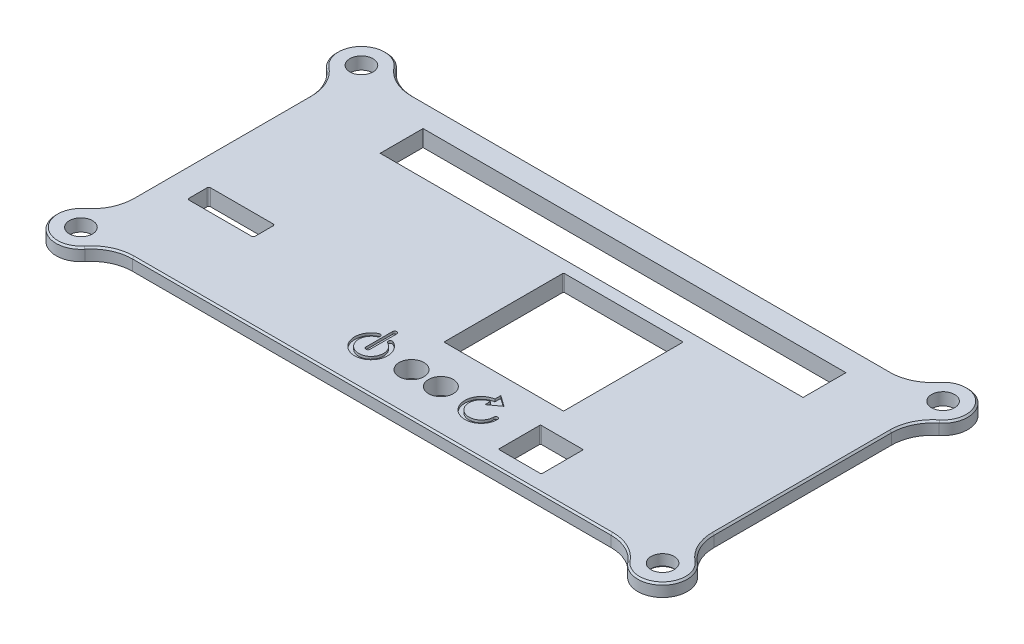
SolidWorks part; units mm, degrees
material "环氧树脂,未充填"
ref_plane "前视基准面" through (0, 0, 0) normal (0, 0, 1) x (1, 0, 0)
ref_plane "上视基准面" through (0, 0, 0) normal (0, 1, 0) x (1, 0, 0)
ref_plane "右视基准面" through (0, 0, 0) normal (1, 0, 0) x (0, 0, -1)
sketch "草图1" plane through (0, 0, 0) normal (0, 1, 0) x (1, 0, 0)
  line L1 (3, 0) -> (67.5, 0)
  line L2 (0, 3) -> (0, 31)
  line L3 (3, 34) -> (67.5, 34)
  line L4 (70.5, 3) -> (70.5, 31)
  arc A0 (3, 34) -> (0, 31) centre (0, 34) ccw
  arc A1 (70.5, 31) -> (67.5, 34) centre (70.5, 34) ccw
  arc A2 (0, 3) -> (3, 0) centre (0, 0) ccw
  arc A3 (67.5, 0) -> (70.5, 3) centre (70.5, 0) ccw
  circle A4 centre (0, 0) radius 1.4
  circle A5 centre (70.5, 0) radius 1.4
  circle A6 centre (70.5, 34) radius 1.4
  circle A7 centre (0, 34) radius 1.4
  dimension "D3" = 2.8
  dimension "D4" = 2.8
  dimension "D5" = 2.8
  dimension "D6" = 2.8
  dimension "D1" = 34
  dimension "D2" = 70.5
extrude "凸台-拉伸1" add sketch "草图1" along normal blind 1.5
fillet "圆角1" radius 5 8 edges at (67.5, 0.75, 0) (3, 0.75, 0) (0, 0.75, -3) (0, 0.75, -31) (3, 0.75, -34) (67.5, 0.75, -34) (70.5, 0.75, -31) (70.5, 0.75, -3)
sketch "草图9" plane through (0, 0, 0) normal (0, -1, 0) x (1, 0, 0)
  line L1 (3.2, -4.5) -> (3.2, -29.5)
  line L11 (66, -32.3) -> (6, -32.3)
  line L12 (68.8, -4.5) -> (68.8, -29.5)
  line L13 (6, -1.7) -> (66, -1.7)
  arc A13 (6, -32.3) -> (3.2, -29.5) centre (6, -29.5) cw
  arc A14 (3.2, -4.5) -> (6, -1.7) centre (6, -4.5) cw
  arc A15 (68.8, -4.5) -> (66, -1.7) centre (66, -4.5) ccw
  arc A16 (68.8, -29.5) -> (66, -32.3) centre (66, -29.5) cw
  dimension "D1" = 2.8
extrude "凸台-拉伸2" add sketch "草图9" along normal blind 0.5
sketch "草图2" plane through (0, 1.5, 0) normal (0, 1, 0) x (1, 0, 0)
  line L3 (48.45, 9.95) -> (34.15, 9.95)
  line L4 (48.55, 10.05) -> (48.55, 24.35)
  line L5 (48.45, 24.45) -> (34.15, 24.45)
  line L6 (34.05, 10.05) -> (34.05, 24.35)
  arc A0 (34.05, 10.05) -> (34.15, 9.95) centre (34.15, 10.05) ccw
  arc A1 (48.45, 9.95) -> (48.55, 10.05) centre (48.45, 10.05) ccw
  arc A2 (48.45, 24.45) -> (48.55, 24.35) centre (48.45, 24.35) cw
  arc A3 (34.15, 24.45) -> (34.05, 24.35) centre (34.15, 24.35) ccw
  point P8 (34.05, 9.95)
  point P11 (48.55, 9.95)
  point P14 (48.55, 24.45)
  dimension "D3" = 0.1
  dimension "D1" = 14.5
  dimension "D2" = 14.5
extrude "切除-拉伸1" cut sketch "草图2" against normal blind 2.5
sketch "草图3" plane through (0, 1.5, 0) normal (0, 1, 0) x (1, 0, 0)
  line L2 (10.37, 31.1) -> (10.37, 25.9)
  line L3 (61.63, 31.1) -> (10.37, 31.1)
  line L5 (61.63, 25.9) -> (10.37, 25.9)
  line L6 (61.63, 31.1) -> (61.63, 25.9)
  point P0 (62.8, 31.1)
  point P8 (62.8, 25.9)
  point P10 (9.2, 25.9)
  point P11 (9.2, 31.1)
extrude "切除-拉伸2" cut sketch "草图3" against normal blind 2.5
sketch "草图4" plane through (0, 1.5, 0) normal (0, 1, 0) x (1, 0, 0)
  line L0 (48.7, 7.1) -> (53.7, 7.1)
  line L1 (53.7, 2) -> (48.7, 2)
  line L2 (53.8, 2.1) -> (53.8, 7)
  line L3 (48.6, 2.1) -> (48.6, 7)
  arc A0 (48.6, 2.1) -> (48.7, 2) centre (48.7, 2.1) ccw
  arc A1 (53.7, 2) -> (53.8, 2.1) centre (53.7, 2.1) ccw
  arc A2 (53.8, 7) -> (53.7, 7.1) centre (53.7, 7) ccw
  arc A3 (48.7, 7.1) -> (48.6, 7) centre (48.7, 7) ccw
  dimension "D1" = 0.1
  dimension "D2" = 0.1
extrude "切除-拉伸3" cut sketch "草图4" against normal blind 2.5
sketch "草图5" plane through (0, 1.5, 0) normal (0, 1, 0) x (1, 0, 0)
  circle A0 centre (34.98, 5.09) radius 1.5
  circle A1 centre (38.54, 5.09) radius 1.5
extrude "切除-拉伸4" cut sketch "草图5" against normal blind 2.5
sketch "草图7" plane through (0, 1.5, 0) normal (0, 1, 0) x (1, 0, 0)
  line L0 (43.1073, 6.5526) -> (43.0982, 5.8686)
  line L1 (29.8339, 4.7171) -> (29.8339, 7.9385)
  line L2 (30.3339, 4.7171) -> (30.3339, 7.9385)
  line L6 (43.1235, 7.7762) -> (43.114, 7.0632)
  line L7 (43.1235, 7.7762) -> (44.4403, 6.84)
  line L9 (44.4403, 6.84) -> (43.0982, 5.8686)
  arc A0 (29.2357, 6.9012) -> (30.9304, 6.902) centre (30.0839, 5.09) ccw
  arc A1 (29.4477, 6.4484) -> (30.7188, 6.449) centre (30.0839, 5.09) ccw
  arc A2 (29.4477, 6.4484) -> (29.2357, 6.9012) centre (29.3417, 6.6748) ccw
  circle A3 centre (30.0839, 5.09) radius 2 construction
  circle A4 centre (30.0839, 5.09) radius 1.5 construction
  arc A5 (30.9304, 6.902) -> (30.7188, 6.449) centre (30.8246, 6.6755) ccw
  arc A6 (30.3339, 7.9385) -> (29.8339, 7.9385) centre (30.0839, 7.9385) ccw
  arc A7 (29.8339, 4.7171) -> (30.3339, 4.7171) centre (30.0839, 4.7171) ccw
  arc A8 (43.114, 7.0632) -> (45.4403, 5.09) centre (43.4403, 5.09) ccw
  arc A9 (43.1073, 6.5526) -> (44.9403, 5.09) centre (43.4403, 5.09) ccw
  arc A10 (45.4403, 5.09) -> (44.9403, 5.09) centre (45.1903, 5.09) ccw
  point P1 (30.4456, 3.0307)
  point P5 (30.8582, 3.6154)
extrude "切除-拉伸5" cut sketch "草图7" against normal blind 0.3
chamfer "倒角1" distance 0.2 angle 45 17 edges at (70.5, 0, 1.4) (66.4201, 1.5, 0.4931) (72.6213, 1.5, 2.1213) (70.9931, 1.5, -4.0799) (70.5, 1.5, -17) (70.9931, 1.5, -29.9201) (72.6213, 1.5, -36.1213) (66.4201, 1.5, -34.4931) (35.25, 1.5, -34) (4.0799, 1.5, -34.4931) (-2.1213, 1.5, -36.1213) (-0.4931, 1.5, -29.9201) (0, 1.5, -17) (-0.4931, 1.5, -4.0799) (-2.1213, 1.5, 2.1213) (4.0799, 1.5, 0.4931) (35.25, 1.5, 0)
sketch "草图10" plane through (0, 1.5, 0) normal (0, 1, 0) x (1, 0, 0)
  line L1 (3.7, 9.4) -> (11.3, 9.4)
  line L2 (3.5, 9.6) -> (3.5, 11.8)
  line L3 (3.7, 12) -> (11.3, 12)
  line L4 (11.5, 11.8) -> (11.5, 9.6)
  arc A0 (3.5, 9.6) -> (3.7, 9.4) centre (3.7, 9.6) ccw
  arc A1 (11.3, 9.4) -> (11.5, 9.6) centre (11.3, 9.6) ccw
  arc A2 (11.5, 11.8) -> (11.3, 12) centre (11.3, 11.8) ccw
  arc A3 (3.7, 12) -> (3.5, 11.8) centre (3.7, 11.8) ccw
  dimension "D1" = 0.2
extrude "切除-拉伸6" cut sketch "草图10" against normal blind 2
